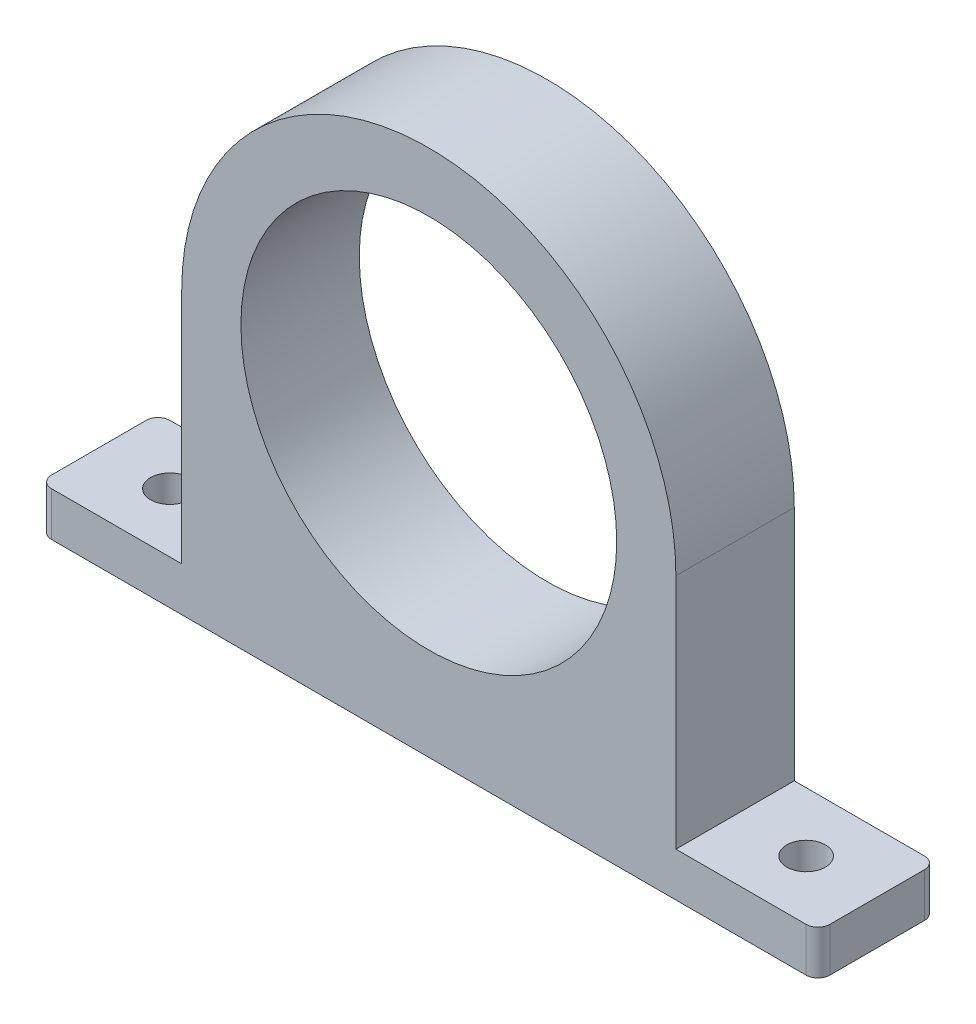
SolidWorks part; units mm, degrees
material "Delrin 2700 NC010, Low Viscosity Acetal Copolymer (SS)"
ref_plane "Front Plane" through (0, 0, 0) normal (0, 0, 1) x (1, 0, 0)
ref_plane "Top Plane" through (0, 0, 0) normal (0, 1, 0) x (1, 0, 0)
ref_plane "Right Plane" through (0, 0, 0) normal (1, 0, 0) x (0, 0, -1)
sketch "Sketch1" plane through (0, 0, 0) normal (0, 0, 1) x (1, 0, 0)
  line L0 (-20.875, 0) -> (-20.875, -20)
  line L1 (-20.875, -20) -> (-32.875, -20)
  line L2 (-32.875, -20) -> (-32.875, -23.72)
  line L3 (-32.875, -23.72) -> (32.875, -23.72)
  line L4 (32.875, -23.72) -> (32.875, -20)
  line L5 (32.875, -20) -> (20.875, -20)
  line L6 (20.875, -20) -> (20.875, 0)
  circle A0 centre (0, 0) radius 15.875
  arc A1 (20.875, 0) -> (-20.875, 0) centre (0, 0) ccw
  dimension "D1" = 31.75
  dimension "D2" = 41.75
  dimension "D3" = 20
  dimension "D5" = 12
  dimension "D4" = 23.72
extrude "Boss-Extrude1" add sketch "Sketch1" along normal blind 10
fillet "Fillet1" radius 1 4 edges at (32.875, -21.86, 0) (32.875, -21.86, 10) (-32.875, -21.86, 0) (-32.875, -21.86, 10)
hole_wizard "#4 Clearance Hole1" positions "Sketch2" profile "Sketch3" hole size "#4" standard "ANSI Inch" end condition through all
sketch "Sketch2" plane through (0, -20, 0) normal (0, 1, 0) x (1, 0, 0)
  line L0 (-32.875, -9) -> (-32.875, -1) construction
  line L3 (32.875, -9) -> (32.875, -1) construction
  point P0 (-26.875, -5)
  point P2 (26.875, -5)
  point P8 (-32.875, -5)
  dimension "D1" = 6
  dimension "D2" = 6
sketch "Sketch3" plane through (-26.875, -20, 5) normal (1, 0, 0) x (0, 0, 1)
  line L0 (0, 0) -> (0, 3.72)
  line L1 (0, 3.72) -> (1.6319, 3.72)
  line L2 (1.6319, 3.72) -> (1.6319, 0)
  line L5 (1.6319, 0) -> (0, 0)
  line L11 (0, -6.35) -> (0, 107.95) construction
  dimension "Thru Hole Dia." = 3.2639
  dimension "Thru Hole Depth" = 3.72
equation "\"D2@Sketch1\"=\"D1@Sketch1\"+(2*5)"
equation "\"D2@Sketch2\"=\"D1@Sketch2\""
